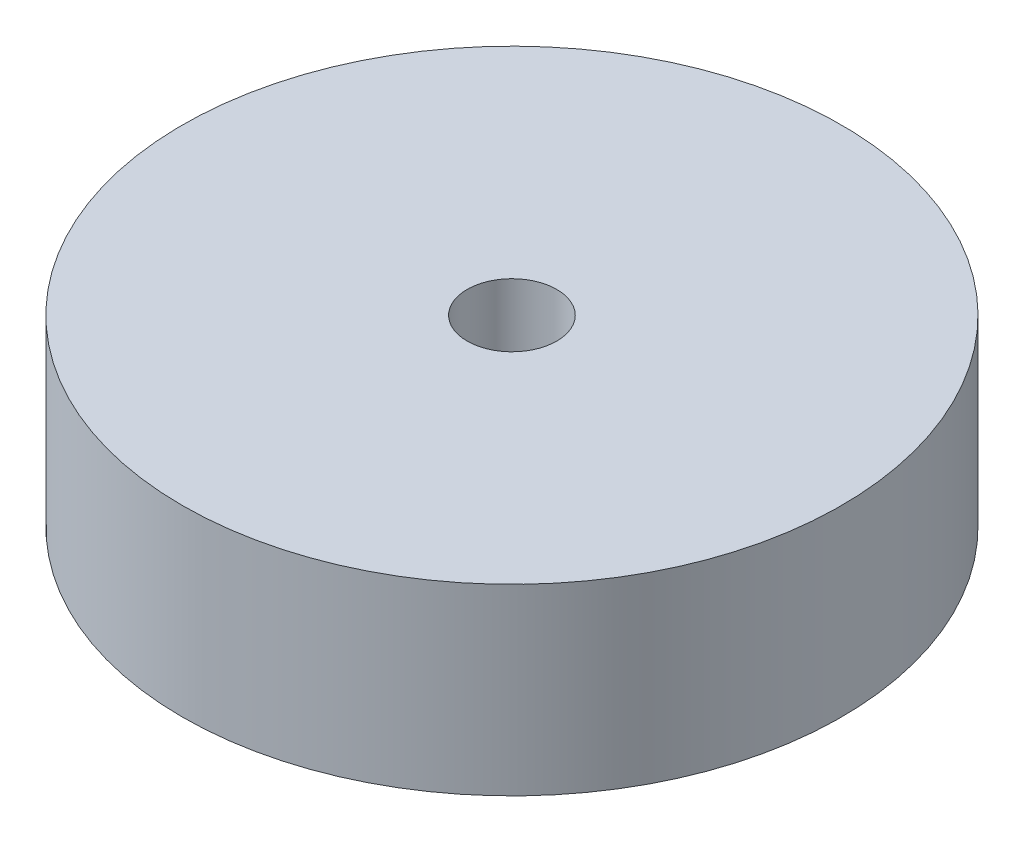
SolidWorks part; units mm, degrees
ref_plane "Front Plane" through (0, 0, 0) normal (0, 0, 1) x (1, 0, 0)
ref_plane "Top Plane" through (0, 0, 0) normal (0, 1, 0) x (1, 0, 0)
ref_plane "Right Plane" through (0, 0, 0) normal (1, 0, 0) x (0, 0, -1)
sketch "Sketch3" plane through (0, 0, 0) normal (0, 1, 0) x (1, 0, 0)
  circle A0 centre (-157.6165, 28.1652) radius 36.5475
extrude "Boss-Extrude1" add sketch "Sketch3" along normal blind 20.32
sketch "Sketch4" plane through (0, 20.32, 0) normal (0, 1, 0) x (1, 0, 0)
  circle A1 centre (-157.6165, 28.1652) radius 4.9687
  circle A3 centre (-157.6165, 28.1652) radius 36.5475 construction
  point P2 (-158.1727, 26.8861)
  point P3 (-157.5053, 29.333)
  point P4 (-162.443, 28.2883)
  point P5 (0, 0)
  point P6 (-162.443, 29.8891)
  dimension "D1" = 0
extrude "Cut-Extrude1" cut sketch "Sketch4" against normal blind 34.544 contours A1
